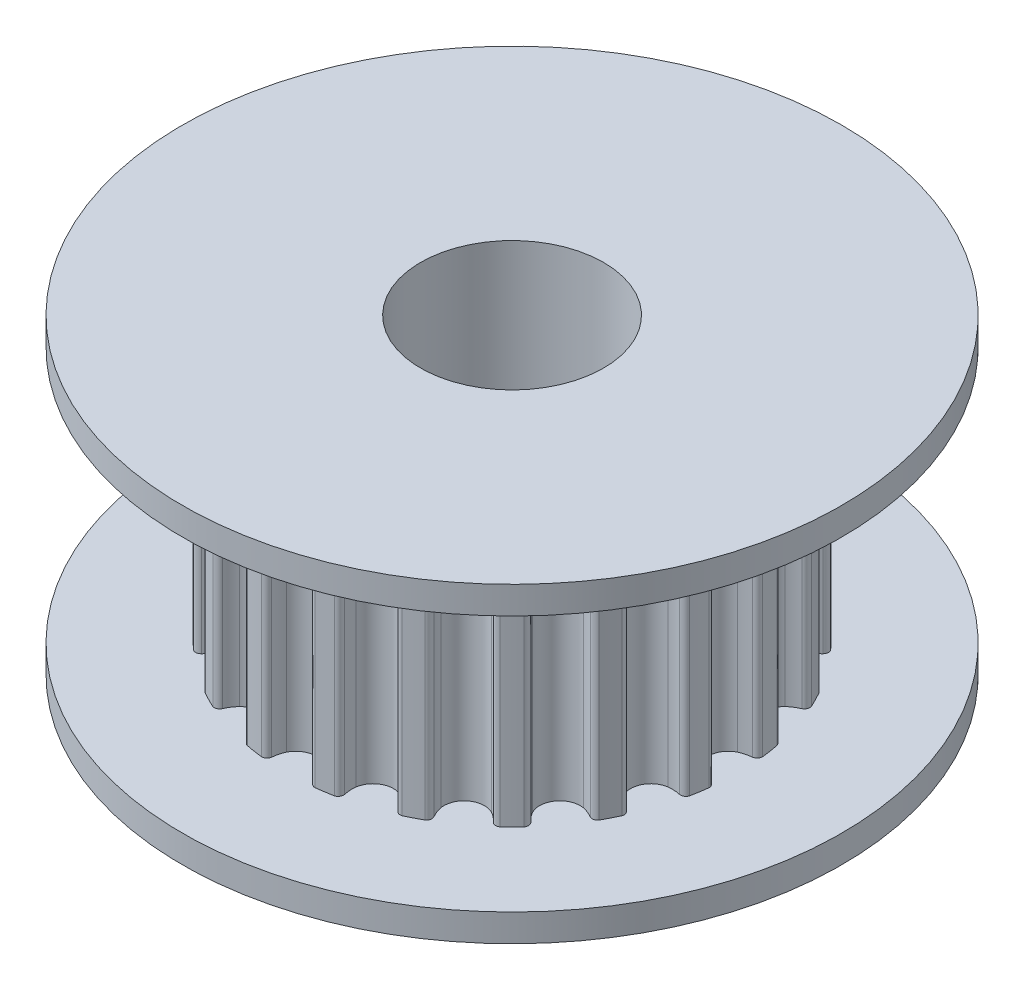
SolidWorks part; units mm, degrees
ref_plane "Front" through (0, 0, 0) normal (0, 0, 1) x (1, 0, 0)
ref_plane "Top" through (0, 0, 0) normal (0, 1, 0) x (1, 0, 0)
ref_plane "Right" through (0, 0, 0) normal (1, 0, 0) x (0, 0, -1)
sketch "Sketch1" plane through (0, 0, 0) normal (0, 0, 1) x (1, 0, 0)
  line L0 (0, 0) -> (0, 8.5) construction
  line L1 (2.5, 0) -> (2.5, 8.5)
  line L2 (2.5, 8.5) -> (9, 8.5)
  line L3 (9, 8.5) -> (9, 7.75)
  line L4 (9, 7.75) -> (6.3662, 7.75)
  line L5 (6.3662, 7.75) -> (6.3662, 0.75)
  line L6 (6.3662, 0.75) -> (9, 0.75)
  line L7 (9, 0.75) -> (9, 0)
  line L8 (9, 0) -> (2.5, 0)
  dimension "D1" = 8.5
  dimension "D2" = 7
  dimension "D3" = 18
  dimension "D4" = 12.7324
  dimension "D5" = 5
revolve "Revolve1" add sketch "Sketch1" angle 360 about L0
sketch "Sketch2" plane through (0, 0.75, 0) normal (0, 1, 0) x (1, 0, 0)
  circle A0 centre (0, 0) radius 6.3662 construction
  circle A1 centre (0, 0) radius 6.3662
  circle A3 centre (0, 0) radius 4.3662
  dimension "D1" = 2
extrude "Cut-Extrude1" cut sketch "Sketch2" along normal up to surface (7 mm away) up to face at (0, 7.75, -9)
sketch "Sketch3" plane through (0, 0.75, 0) normal (0, 1, 0) x (1, 0, 0)
  circle A0 centre (0, 0) radius 1.5
  arc A1 (6.1135, -0.7303) -> (5.9829, -0.5816) centre (5.9635, -0.7303) ccw
  arc A2 (5.659, -0.4964) -> (5.9829, -0.5816) centre (6.0717, 0.4144) ccw
  arc A3 (5.3522, 0) -> (5.659, -0.4964) centre (5.9072, 0) ccw
  arc A4 (5.659, 0.4964) -> (5.3522, 0) centre (5.9072, 0) ccw
  arc A5 (5.9829, 0.5816) -> (5.659, 0.4964) centre (6.0717, -0.4144) ccw
  arc A6 (5.9829, 0.5816) -> (6.1135, 0.7303) centre (5.9635, 0.7303) ccw
  arc A7 (6.1135, 0.7303) -> (6.0399, 1.1946) centre (0.0442, 0.007) ccw
  arc A8 (6.0399, 1.1946) -> (5.8698, 1.2957) centre (5.8973, 1.1482) ccw
  arc A9 (5.5354, 1.2766) -> (5.8698, 1.2957) centre (5.6465, 2.2704) ccw
  arc A10 (5.0902, 1.6539) -> (5.5354, 1.2766) centre (5.6181, 1.8254) ccw
  arc A11 (5.2286, 2.2208) -> (5.0902, 1.6539) centre (5.6181, 1.8254) ccw
  arc A12 (5.5103, 2.4019) -> (5.2286, 2.2208) centre (5.9026, 1.4821) ccw
  arc A13 (5.5103, 2.4019) -> (5.5886, 2.5838) centre (5.4459, 2.5374) ccw
  arc A14 (5.5886, 2.5838) -> (5.3752, 3.0025) centre (0.0399, 0.0203) ccw
  arc A15 (5.3752, 3.0025) -> (5.1821, 3.0461) centre (5.2538, 2.9144) ccw
  arc A16 (4.87, 2.9247) -> (5.1821, 3.0461) centre (4.6685, 3.9042) ccw
  arc A17 (4.33, 3.1459) -> (4.87, 2.9247) centre (4.779, 3.4722) ccw
  arc A18 (4.2864, 3.7279) -> (4.33, 3.1459) centre (4.779, 3.4722) ccw
  arc A19 (4.4984, 3.9872) -> (4.2864, 3.7279) centre (5.1557, 3.2336) ccw
  arc A20 (4.4984, 3.9872) -> (4.5166, 4.1843) centre (4.3953, 4.0961) ccw
  arc A21 (4.5166, 4.1843) -> (4.1843, 4.5166) centre (0.0317, 0.0317) ccw
  arc A22 (4.1843, 4.5166) -> (3.9872, 4.4984) centre (4.0961, 4.3953) ccw
  arc A23 (3.7279, 4.2864) -> (3.9872, 4.4984) centre (3.2336, 5.1557) ccw
  arc A24 (3.1459, 4.33) -> (3.7279, 4.2864) centre (3.4722, 4.779) ccw
  arc A25 (2.9247, 4.87) -> (3.1459, 4.33) centre (3.4722, 4.779) ccw
  arc A26 (3.0461, 5.1821) -> (2.9247, 4.87) centre (3.9042, 4.6685) ccw
  arc A27 (3.0461, 5.1821) -> (3.0025, 5.3752) centre (2.9144, 5.2538) ccw
  arc A28 (3.0025, 5.3752) -> (2.5838, 5.5886) centre (0.0203, 0.0399) ccw
  arc A29 (2.5838, 5.5886) -> (2.4019, 5.5103) centre (2.5374, 5.4459) ccw
  arc A30 (2.2208, 5.2286) -> (2.4019, 5.5103) centre (1.4821, 5.9026) ccw
  arc A31 (1.6539, 5.0902) -> (2.2208, 5.2286) centre (1.8254, 5.6181) ccw
  arc A32 (1.2766, 5.5354) -> (1.6539, 5.0902) centre (1.8254, 5.6181) ccw
  arc A33 (1.2957, 5.8698) -> (1.2766, 5.5354) centre (2.2704, 5.6465) ccw
  arc A34 (1.2957, 5.8698) -> (1.1946, 6.0399) centre (1.1482, 5.8973) ccw
  arc A35 (1.1946, 6.0399) -> (0.7303, 6.1135) centre (0.007, 0.0442) ccw
  arc A36 (0.7303, 6.1135) -> (0.5816, 5.9829) centre (0.7303, 5.9635) ccw
  arc A37 (0.4964, 5.659) -> (0.5816, 5.9829) centre (-0.4144, 6.0717) ccw
  arc A38 (0, 5.3522) -> (0.4964, 5.659) centre (0, 5.9072) ccw
  arc A39 (-0.4964, 5.659) -> (0, 5.3522) centre (0, 5.9072) ccw
  arc A40 (-0.5816, 5.9829) -> (-0.4964, 5.659) centre (0.4144, 6.0717) ccw
  arc A41 (-0.5816, 5.9829) -> (-0.7303, 6.1135) centre (-0.7303, 5.9635) ccw
  arc A42 (-0.7303, 6.1135) -> (-1.1946, 6.0399) centre (-0.007, 0.0442) ccw
  arc A43 (-1.1946, 6.0399) -> (-1.2957, 5.8698) centre (-1.1482, 5.8973) ccw
  arc A44 (-1.2766, 5.5354) -> (-1.2957, 5.8698) centre (-2.2704, 5.6465) ccw
  arc A45 (-1.6539, 5.0902) -> (-1.2766, 5.5354) centre (-1.8254, 5.6181) ccw
  arc A46 (-2.2208, 5.2286) -> (-1.6539, 5.0902) centre (-1.8254, 5.6181) ccw
  arc A47 (-2.4019, 5.5103) -> (-2.2208, 5.2286) centre (-1.4821, 5.9026) ccw
  arc A48 (-2.4019, 5.5103) -> (-2.5838, 5.5886) centre (-2.5374, 5.4459) ccw
  arc A49 (-2.5838, 5.5886) -> (-3.0025, 5.3752) centre (-0.0203, 0.0399) ccw
  arc A50 (-3.0025, 5.3752) -> (-3.0461, 5.1821) centre (-2.9144, 5.2538) ccw
  arc A51 (-2.9247, 4.87) -> (-3.0461, 5.1821) centre (-3.9042, 4.6685) ccw
  arc A52 (-3.1459, 4.33) -> (-2.9247, 4.87) centre (-3.4722, 4.779) ccw
  arc A53 (-3.7279, 4.2864) -> (-3.1459, 4.33) centre (-3.4722, 4.779) ccw
  arc A54 (-3.9872, 4.4984) -> (-3.7279, 4.2864) centre (-3.2336, 5.1557) ccw
  arc A55 (-3.9872, 4.4984) -> (-4.1843, 4.5166) centre (-4.0961, 4.3953) ccw
  arc A56 (-4.1843, 4.5166) -> (-4.5166, 4.1843) centre (-0.0317, 0.0317) ccw
  arc A57 (-4.5166, 4.1843) -> (-4.4984, 3.9872) centre (-4.3953, 4.0961) ccw
  arc A58 (-4.2864, 3.7279) -> (-4.4984, 3.9872) centre (-5.1557, 3.2336) ccw
  arc A59 (-4.33, 3.1459) -> (-4.2864, 3.7279) centre (-4.779, 3.4722) ccw
  arc A60 (-4.87, 2.9247) -> (-4.33, 3.1459) centre (-4.779, 3.4722) ccw
  arc A61 (-5.1821, 3.0461) -> (-4.87, 2.9247) centre (-4.6685, 3.9042) ccw
  arc A62 (-5.1821, 3.0461) -> (-5.3752, 3.0025) centre (-5.2538, 2.9144) ccw
  arc A63 (-5.3752, 3.0025) -> (-5.5886, 2.5838) centre (-0.0399, 0.0203) ccw
  arc A64 (-5.5886, 2.5838) -> (-5.5103, 2.4019) centre (-5.4459, 2.5374) ccw
  arc A65 (-5.2286, 2.2208) -> (-5.5103, 2.4019) centre (-5.9026, 1.4821) ccw
  arc A66 (-5.0902, 1.6539) -> (-5.2286, 2.2208) centre (-5.6181, 1.8254) ccw
  arc A67 (-5.5354, 1.2766) -> (-5.0902, 1.6539) centre (-5.6181, 1.8254) ccw
  arc A68 (-5.8698, 1.2957) -> (-5.5354, 1.2766) centre (-5.6465, 2.2704) ccw
  arc A69 (-5.8698, 1.2957) -> (-6.0399, 1.1946) centre (-5.8973, 1.1482) ccw
  arc A70 (-6.0399, 1.1946) -> (-6.1135, 0.7303) centre (-0.0442, 0.007) ccw
  arc A71 (-6.1135, 0.7303) -> (-5.9829, 0.5816) centre (-5.9635, 0.7303) ccw
  arc A72 (-5.659, 0.4964) -> (-5.9829, 0.5816) centre (-6.0717, -0.4144) ccw
  arc A73 (-5.3522, 0) -> (-5.659, 0.4964) centre (-5.9072, 0) ccw
  arc A74 (-5.659, -0.4964) -> (-5.3522, 0) centre (-5.9072, 0) ccw
  arc A75 (-5.9829, -0.5816) -> (-5.659, -0.4964) centre (-6.0717, 0.4144) ccw
  arc A76 (-5.9829, -0.5816) -> (-6.1135, -0.7303) centre (-5.9635, -0.7303) ccw
  arc A77 (-6.1135, -0.7303) -> (-6.0399, -1.1946) centre (-0.0442, -0.007) ccw
  arc A78 (-6.0399, -1.1946) -> (-5.8698, -1.2957) centre (-5.8973, -1.1482) ccw
  arc A79 (-5.5354, -1.2766) -> (-5.8698, -1.2957) centre (-5.6465, -2.2704) ccw
  arc A80 (-5.0902, -1.6539) -> (-5.5354, -1.2766) centre (-5.6181, -1.8254) ccw
  arc A81 (-5.2286, -2.2208) -> (-5.0902, -1.6539) centre (-5.6181, -1.8254) ccw
  arc A82 (-5.5103, -2.4019) -> (-5.2286, -2.2208) centre (-5.9026, -1.4821) ccw
  arc A83 (-5.5103, -2.4019) -> (-5.5886, -2.5838) centre (-5.4459, -2.5374) ccw
  arc A84 (-5.5886, -2.5838) -> (-5.3752, -3.0025) centre (-0.0399, -0.0203) ccw
  arc A85 (-5.3752, -3.0025) -> (-5.1821, -3.0461) centre (-5.2538, -2.9144) ccw
  arc A86 (-4.87, -2.9247) -> (-5.1821, -3.0461) centre (-4.6685, -3.9042) ccw
  arc A87 (-4.33, -3.1459) -> (-4.87, -2.9247) centre (-4.779, -3.4722) ccw
  arc A88 (-4.2864, -3.7279) -> (-4.33, -3.1459) centre (-4.779, -3.4722) ccw
  arc A89 (-4.4984, -3.9872) -> (-4.2864, -3.7279) centre (-5.1557, -3.2336) ccw
  arc A90 (-4.4984, -3.9872) -> (-4.5166, -4.1843) centre (-4.3953, -4.0961) ccw
  arc A91 (-4.5166, -4.1843) -> (-4.1843, -4.5166) centre (-0.0317, -0.0317) ccw
  arc A92 (-4.1843, -4.5166) -> (-3.9872, -4.4984) centre (-4.0961, -4.3953) ccw
  arc A93 (-3.7279, -4.2864) -> (-3.9872, -4.4984) centre (-3.2336, -5.1557) ccw
  arc A94 (-3.1459, -4.33) -> (-3.7279, -4.2864) centre (-3.4722, -4.779) ccw
  arc A95 (-2.9247, -4.87) -> (-3.1459, -4.33) centre (-3.4722, -4.779) ccw
  arc A96 (-3.0461, -5.1821) -> (-2.9247, -4.87) centre (-3.9042, -4.6685) ccw
  arc A97 (-3.0461, -5.1821) -> (-3.0025, -5.3752) centre (-2.9144, -5.2538) ccw
  arc A98 (-3.0025, -5.3752) -> (-2.5838, -5.5886) centre (-0.0203, -0.0399) ccw
  arc A99 (-2.5838, -5.5886) -> (-2.4019, -5.5103) centre (-2.5374, -5.4459) ccw
  arc A100 (-2.2208, -5.2286) -> (-2.4019, -5.5103) centre (-1.4821, -5.9026) ccw
  arc A101 (-1.6539, -5.0902) -> (-2.2208, -5.2286) centre (-1.8254, -5.6181) ccw
  arc A102 (-1.2766, -5.5354) -> (-1.6539, -5.0902) centre (-1.8254, -5.6181) ccw
  arc A103 (-1.2957, -5.8698) -> (-1.2766, -5.5354) centre (-2.2704, -5.6465) ccw
  arc A104 (-1.2957, -5.8698) -> (-1.1946, -6.0399) centre (-1.1482, -5.8973) ccw
  arc A105 (-1.1946, -6.0399) -> (-0.7303, -6.1135) centre (-0.007, -0.0442) ccw
  arc A106 (-0.7303, -6.1135) -> (-0.5816, -5.9829) centre (-0.7303, -5.9635) ccw
  arc A107 (-0.4964, -5.659) -> (-0.5816, -5.9829) centre (0.4144, -6.0717) ccw
  arc A108 (0, -5.3522) -> (-0.4964, -5.659) centre (0, -5.9072) ccw
  arc A109 (0.4964, -5.659) -> (0, -5.3522) centre (0, -5.9072) ccw
  arc A110 (0.5816, -5.9829) -> (0.4964, -5.659) centre (-0.4144, -6.0717) ccw
  arc A111 (0.5816, -5.9829) -> (0.7303, -6.1135) centre (0.7303, -5.9635) ccw
  arc A112 (0.7303, -6.1135) -> (1.1946, -6.0399) centre (0.007, -0.0442) ccw
  arc A113 (1.1946, -6.0399) -> (1.2957, -5.8698) centre (1.1482, -5.8973) ccw
  arc A114 (1.2766, -5.5354) -> (1.2957, -5.8698) centre (2.2704, -5.6465) ccw
  arc A115 (1.6539, -5.0902) -> (1.2766, -5.5354) centre (1.8254, -5.6181) ccw
  arc A116 (2.2208, -5.2286) -> (1.6539, -5.0902) centre (1.8254, -5.6181) ccw
  arc A117 (2.4019, -5.5103) -> (2.2208, -5.2286) centre (1.4821, -5.9026) ccw
  arc A118 (2.4019, -5.5103) -> (2.5838, -5.5886) centre (2.5374, -5.4459) ccw
  arc A119 (2.5838, -5.5886) -> (3.0025, -5.3752) centre (0.0203, -0.0399) ccw
  arc A120 (3.0025, -5.3752) -> (3.0461, -5.1821) centre (2.9144, -5.2538) ccw
  arc A121 (2.9247, -4.87) -> (3.0461, -5.1821) centre (3.9042, -4.6685) ccw
  arc A122 (3.1459, -4.33) -> (2.9247, -4.87) centre (3.4722, -4.779) ccw
  arc A123 (3.7279, -4.2864) -> (3.1459, -4.33) centre (3.4722, -4.779) ccw
  arc A124 (3.9872, -4.4984) -> (3.7279, -4.2864) centre (3.2336, -5.1557) ccw
  arc A125 (3.9872, -4.4984) -> (4.1843, -4.5166) centre (4.0961, -4.3953) ccw
  arc A126 (4.1843, -4.5166) -> (4.5166, -4.1843) centre (0.0317, -0.0317) ccw
  arc A127 (4.5166, -4.1843) -> (4.4984, -3.9872) centre (4.3953, -4.0961) ccw
  arc A128 (4.2864, -3.7279) -> (4.4984, -3.9872) centre (5.1557, -3.2336) ccw
  arc A129 (4.33, -3.1459) -> (4.2864, -3.7279) centre (4.779, -3.4722) ccw
  arc A130 (4.87, -2.9247) -> (4.33, -3.1459) centre (4.779, -3.4722) ccw
  arc A131 (5.1821, -3.0461) -> (4.87, -2.9247) centre (4.6685, -3.9042) ccw
  arc A132 (5.1821, -3.0461) -> (5.3752, -3.0025) centre (5.2538, -2.9144) ccw
  arc A133 (5.3752, -3.0025) -> (5.5886, -2.5838) centre (0.0399, -0.0203) ccw
  arc A134 (5.5886, -2.5838) -> (5.5103, -2.4019) centre (5.4459, -2.5374) ccw
  arc A135 (5.2286, -2.2208) -> (5.5103, -2.4019) centre (5.9026, -1.4821) ccw
  arc A136 (5.0902, -1.6539) -> (5.2286, -2.2208) centre (5.6181, -1.8254) ccw
  arc A137 (5.5354, -1.2766) -> (5.0902, -1.6539) centre (5.6181, -1.8254) ccw
  arc A138 (5.8698, -1.2957) -> (5.5354, -1.2766) centre (5.6465, -2.2704) ccw
  arc A139 (5.8698, -1.2957) -> (6.0399, -1.1946) centre (5.8973, -1.1482) ccw
  arc A140 (6.0399, -1.1946) -> (6.1135, -0.7303) centre (0.0442, -0.007) ccw
  circle A141 centre (0, 0) radius 4.3662 construction
  circle A142 centre (0, 0) radius 4.3662
extrude "Boss-Extrude1" add sketch "Sketch3" along normal up to surface (7 mm away) contours A139 A140 A1 A2 A3 A4 A5 A6 A7 A8 A9 A10 A11 A12 A13 A14 A15 A16 A17 A18 A19 A20 A21 A22 A23 A24 A25 A26 A27 A28 A29 A30 A31 A32 A33 A34 A35 A36 A37 A38 A39 A40 A41 A42 A43 A44 A45 A46 A47 A48 A49 up to face at (0, 7.75, -9)
sketch "innermost_diameter" plane through (0, 7.75, 0) normal (0, -1, 0) x (1, 0, 0)
  circle A0 centre (0, 0) radius 5.3522
sketch "approx pitch diameter" plane through (0, 8.5, 0) normal (0, 1, 0) x (1, 0, 0)
  circle A0 centre (0, 0) radius 5.625
  dimension "D1" = 11.25
equation "\"D4@Sketch1\"=20*2/3.14159"
